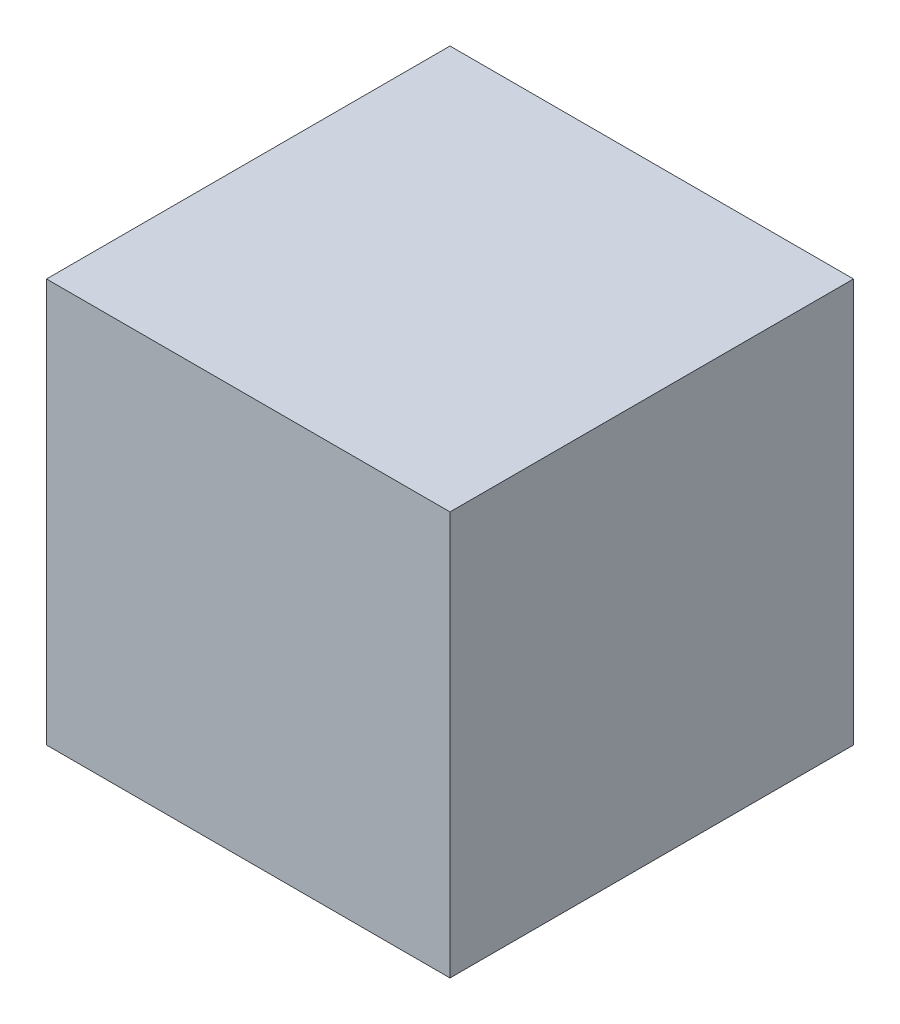
SolidWorks part; units mm, degrees
ref_plane "Front Plane" through (0, 0, 0) normal (0, 0, 1) x (1, 0, 0)
ref_plane "Top Plane" through (0, 0, 0) normal (0, 1, 0) x (1, 0, 0)
ref_plane "Right Plane" through (0, 0, 0) normal (1, 0, 0) x (0, 0, -1)
sketch "Sketch1" plane through (0, 0, 0) normal (0, 1, 0) x (1, 0, 0)
  line L0 (-127, 127.1) -> (127, 127.1)
  line L1 (-126.9, 127) -> (127, 127)
  line L2 (-127, 127) -> (-127, -127)
  line L3 (-127, -127) -> (127, -127)
  line L4 (127, 127) -> (127, -126.9)
  line L5 (-127, 127) -> (127, -127) construction
  line L6 (-127, -127) -> (127, 127) construction
  line L7 (-126.9, 127) -> (-126.9, -126.9)
  line L8 (-126.9, -126.9) -> (127, -126.9)
  line L9 (127.1, 127) -> (127.1, -127)
  line L10 (-126.9293, 127.0707) -> (127.0707, -126.9293) construction
  line L11 (-127.0707, -126.9293) -> (126.9293, 127.0707) construction
  line L12 (127, -127) -> (127.1, -127)
  line L13 (127, 127) -> (127, -127) construction
  line L14 (127, 127.1) -> (127.1, 127.1)
  line L15 (127.1, 127.1) -> (127.1, 127)
  line L16 (-127, 127) -> (127, 127) construction
  line L17 (-127, 127) -> (-127, 127.1)
  line L18 (-127, -126.9) -> (127, -126.9) construction
  line L19 (-126.9, 127) -> (-126.9, -127) construction
  point P0 (0, 0)
  point P20 (-127.372, -127.0142)
  dimension "D1" = 254
  dimension "D2" = 254
  dimension "D3" = 0.1
extrude "Boss-Extrude1" add sketch "Sketch1" along normal blind 254
sketch "Sketch3" plane through (0, 254, 0) normal (0, 1, 0) x (1, 0, 0)
  line L1 (-127, 127.1) -> (127.1, 127.1)
  line L2 (-127, 127.1) -> (-127, -127)
  line L3 (-127, -127) -> (127.1, -127)
  line L4 (127.1, 127.1) -> (127.1, -127)
extrude "Boss-Extrude2" add sketch "Sketch3" along normal blind 0.1
sketch "Sketch4" plane through (0, 0, 0) normal (0, -1, 0) x (1, 0, 0)
  line L1 (-127, 127) -> (127.1, 127)
  line L2 (-127, 127) -> (-127, -127.1)
  line L3 (-127, -127.1) -> (127.1, -127.1)
  line L4 (127.1, 127) -> (127.1, -127.1)
extrude "Boss-Extrude3" add sketch "Sketch4" along normal blind 0.1
